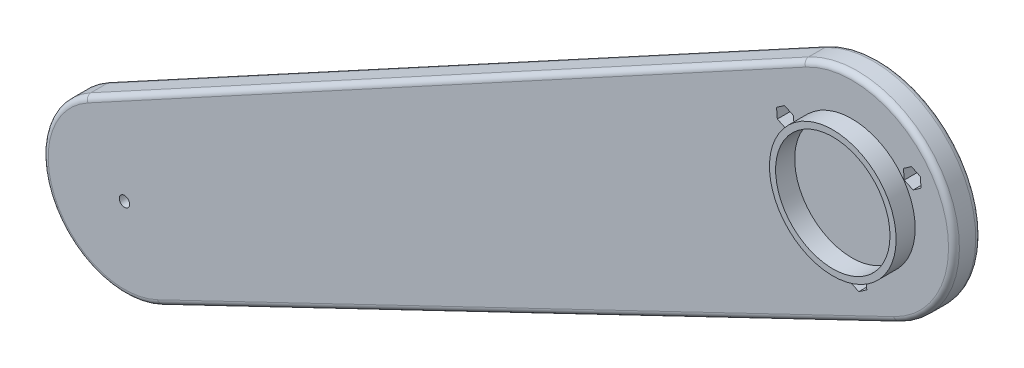
SolidWorks part; units mm, degrees
ref_plane "Front Plane" through (0, 0, 0) normal (0, 0, 1) x (1, 0, 0)
ref_plane "Top Plane" through (0, 0, 0) normal (0, 1, 0) x (1, 0, 0)
ref_plane "Right Plane" through (0, 0, 0) normal (1, 0, 0) x (0, 0, -1)
sketch "Sketch1" plane through (0, 0, 0) normal (0, 0, 1) x (1, 0, 0)
  line L0 (-281.4324, -110.2081) -> (-17.9006, 32.9518)
  line L1 (-254.127, -163.6138) -> (16.2311, -33.8053)
  arc A2 (16.2311, -33.8053) -> (-17.9006, 32.9518) centre (0, 0) ccw
  arc A3 (-281.4324, -110.2081) -> (-254.127, -163.6138) centre (-267.1119, -136.5695) ccw
  dimension "D1" = 75
  dimension "D2" = 60
  dimension "D3" = 300
extrude "Boss-Extrude1" add sketch "Sketch1" along normal blind 10
fillet "Fillet1" radius 2 8 edges at (-149.6665, -38.6281, 10) (33.389, 17.0712, 10) (-118.9479, -98.7095, 10) (-293.8231, -150.2264, 10) (-118.9479, -98.7095, 0) (33.389, 17.0712, 0) (-149.6665, -38.6281, 0) (-293.8231, -150.2264, 0)
sketch "Sketch3" plane through (0, 0, 10) normal (0, 0, 1) x (1, 0, 0)
  circle A0 centre (-267.1119, -136.5695) radius 1.9
  dimension "D1" = 3.8
extrude "Cut-Extrude3" cut sketch "Sketch3" against normal blind 240
sketch "Sketch4" plane through (0, 0, 10) normal (0, 0, 1) x (1, 0, 0)
  line L18 (0, 0) -> (22.1781, 15.3991)
  line L19 (1.9491, -23.3388) -> (-0.9916, -25.3806)
  line L20 (19.2374, 13.3573) -> (22.476, 11.8315)
  line L21 (22.476, 11.8315) -> (25.4167, 13.8733)
  line L22 (25.4167, 13.8733) -> (25.1187, 17.4409)
  line L23 (25.1187, 17.4409) -> (21.8801, 18.9667)
  line L24 (21.8801, 18.9667) -> (18.9395, 16.9249)
  line L25 (18.9395, 16.9249) -> (19.2374, 13.3573)
  line L26 (-0.9916, -25.3806) -> (-0.6937, -28.9481)
  line L27 (-0.6937, -28.9481) -> (2.5449, -30.4739)
  line L28 (2.5449, -30.4739) -> (5.4856, -28.4321)
  line L29 (5.4856, -28.4321) -> (5.1876, -24.8645)
  line L30 (5.1876, -24.8645) -> (1.9491, -23.3388)
  line L31 (-21.1865, 9.9815) -> (-21.4844, 13.549)
  line L32 (-21.4844, 13.549) -> (-24.723, 15.0748)
  line L33 (-24.723, 15.0748) -> (-27.6636, 13.033)
  line L34 (-27.6636, 13.033) -> (-27.3657, 9.4654)
  line L35 (-27.3657, 9.4654) -> (-24.1271, 7.9396)
  line L36 (-24.1271, 7.9396) -> (-21.1865, 9.9815)
  circle A2 centre (22.1781, 15.3991) radius 3.1004 construction
  point P22 (0, 0)
  point P26 (0, 0)
  dimension "D1" = 3.58
  dimension "D2" = 27
  dimension "D3" = 3
extrude "Cut-Extrude4" cut sketch "Sketch4" against normal blind 5
sketch "Sketch6" plane through (0, 0, 10) normal (0, 0, 1) x (1, 0, 0)
  circle A0 centre (2.247, -26.9063) radius 1.75
  circle A1 centre (-24.4251, 11.5072) radius 1.75
  circle A2 centre (22.1781, 15.3991) radius 1.75
  point P14 (0, 0)
  dimension "D1" = 3.5
  dimension "D2" = 3
extrude "Cut-Extrude8" cut sketch "Sketch6" against normal blind 10 contours A2 | A0 | A1
sketch "Sketch7" plane through (0, 0, 10) normal (0, 0, 1) x (1, 0, 0)
  circle A0 centre (0, 0) radius 23.25
  circle A1 centre (0, 0) radius 21
  dimension "D1" = 46.5
  dimension "D2" = 42
extrude "Boss-Extrude2" add sketch "Sketch7" along normal blind 7
sketch "Sketch8" plane through (0, 0, 0) normal (0, 0, -1) x (-1, 0, 0)
  line L7 (270.6351, -137.2049) -> (269.4238, -133.8361)
  line L8 (269.4238, -133.8361) -> (265.9007, -133.2006)
  line L9 (265.9007, -133.2006) -> (263.5888, -135.934)
  line L10 (263.5888, -135.934) -> (264.8, -139.3029)
  line L11 (264.8, -139.3029) -> (268.3232, -139.9384)
  line L12 (268.3232, -139.9384) -> (270.6351, -137.2049)
  circle A2 centre (267.1119, -136.5695) radius 3.1004 construction
  dimension "D1" = 3.58
extrude "Cut-Extrude9" cut sketch "Sketch8" against normal blind 5
